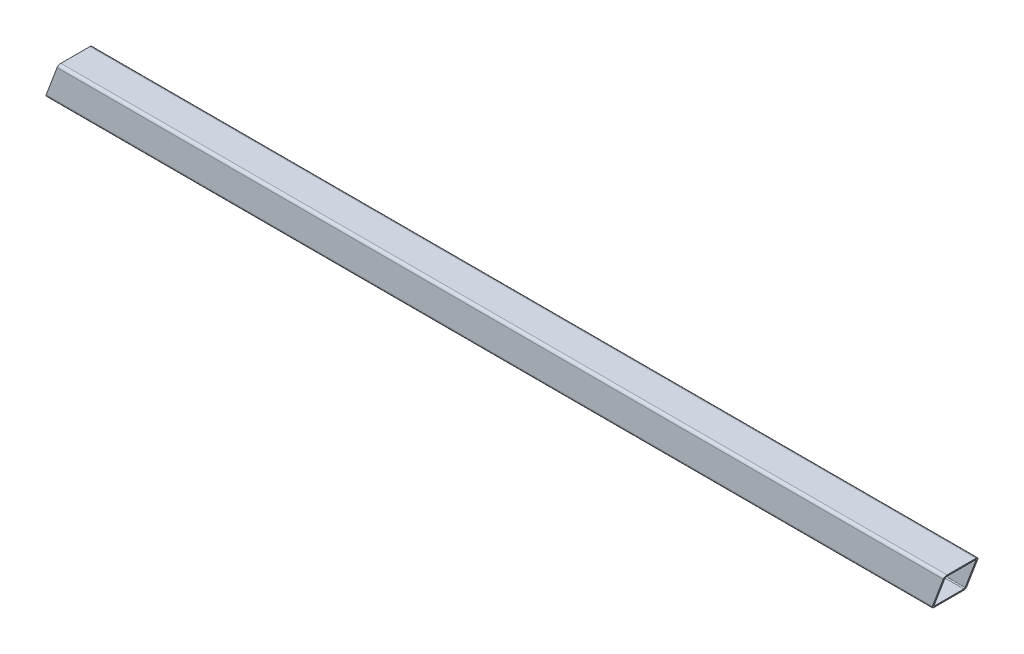
SolidWorks part; units mm, degrees
material "Plain Carbon Steel"
ref_plane "Front Plane" through (0, 0, 0) normal (0, 0, 1) x (1, 0, 0)
ref_plane "Top Plane" through (0, 0, 0) normal (0, 1, 0) x (1, 0, 0)
ref_plane "Right Plane" through (0, 0, 0) normal (1, 0, 0) x (0, 0, -1)
sketch "Sketch1" plane through (0, 0, 0) normal (1, 0, 0) x (0, 0, -1)
  line L0 (0, 2.54) -> (0, 29.21)
  line L1 (-2.54, 31.75) -> (-29.21, 31.75)
  line L2 (-31.75, 29.21) -> (-31.75, 2.54)
  line L3 (-29.21, 0) -> (-2.54, 0)
  line L4 (-1.651, 2.54) -> (-1.651, 29.21)
  line L5 (-2.54, 30.099) -> (-29.21, 30.099)
  line L6 (-30.099, 29.21) -> (-30.099, 2.54)
  line L7 (-29.21, 1.651) -> (-2.54, 1.651)
  arc A0 (-31.75, 2.54) -> (-29.21, 0) centre (-29.21, 2.54) ccw
  arc A1 (0, 2.54) -> (-2.54, 0) centre (-2.54, 2.54) cw
  arc A2 (0, 29.21) -> (-2.54, 31.75) centre (-2.54, 29.21) ccw
  arc A3 (-31.75, 29.21) -> (-29.21, 31.75) centre (-29.21, 29.21) cw
  arc A4 (-1.651, 29.21) -> (-2.54, 30.099) centre (-2.54, 29.21) ccw
  arc A5 (-30.099, 29.21) -> (-29.21, 30.099) centre (-29.21, 29.21) cw
  arc A6 (-30.099, 2.54) -> (-29.21, 1.651) centre (-29.21, 2.54) ccw
  arc A7 (-1.651, 2.54) -> (-2.54, 1.651) centre (-2.54, 2.54) cw
  point P12 (0, 0)
  point P15 (0, 31.75)
  point P18 (-31.75, 31.75)
  dimension "D3" = 2.54
  dimension "D1" = 31.75
  dimension "D2" = 31.75
  dimension "D4" = 1.651
extrude "Boss-Extrude1" add sketch "Sketch1" along normal blind 1320.8
sketch "Sketch2" plane through (1320.8, 0, 0) normal (1, 0, 0) x (0, 0, -1)
  line L0 (-31.75, 15.875) -> (0, 15.875)
  line L1 (-31.75, 29.21) -> (-31.75, 2.54) construction
  line L2 (0, 2.54) -> (0, 29.21) construction
scale "Scale2" scale about centroid uniform scaling no x scale factor 1 y scale factor 0.4 z scale factor 0.4
sketch "Sketch3" plane through (0, 0, 22.225) normal (0, 0, 1) x (1, 0, 0)
  line L6 (896.669, 22.225) -> (891.9223, 9.525)
  line L7 (1320.8, 22.225) -> (0, 22.225) construction
  line L8 (1140.7806, 675.3591) -> (896.2356, 21.0655) construction
  line L9 (1320.8, 9.525) -> (0, 9.525) construction
  line L10 (896.669, 22.225) -> (863.5553, 22.225)
  line L11 (863.5553, 22.225) -> (863.5553, 9.525)
  line L12 (863.5553, 9.525) -> (891.9223, 9.525)
extrude "Cut-Extrude1" cut sketch "Sketch3" against normal through all
sketch "Sketch4" plane through (0, 0, 22.225) normal (0, 0, 1) x (1, 0, 0)
  line L0 (1217.3157, 9.525) -> (1320.8, 9.525)
  line L1 (1320.8, 9.525) -> (1320.8, 22.225)
  line L2 (1320.8, 22.225) -> (1222.0624, 22.225)
  line L3 (1430.7368, 580.5448) -> (1217.3157, 9.525) construction
  line L4 (1320.8, 22.225) -> (896.669, 22.225) construction
  line L5 (1222.0624, 22.225) -> (1217.3157, 9.525)
extrude "Cut-Extrude2" cut sketch "Sketch4" against normal through all
